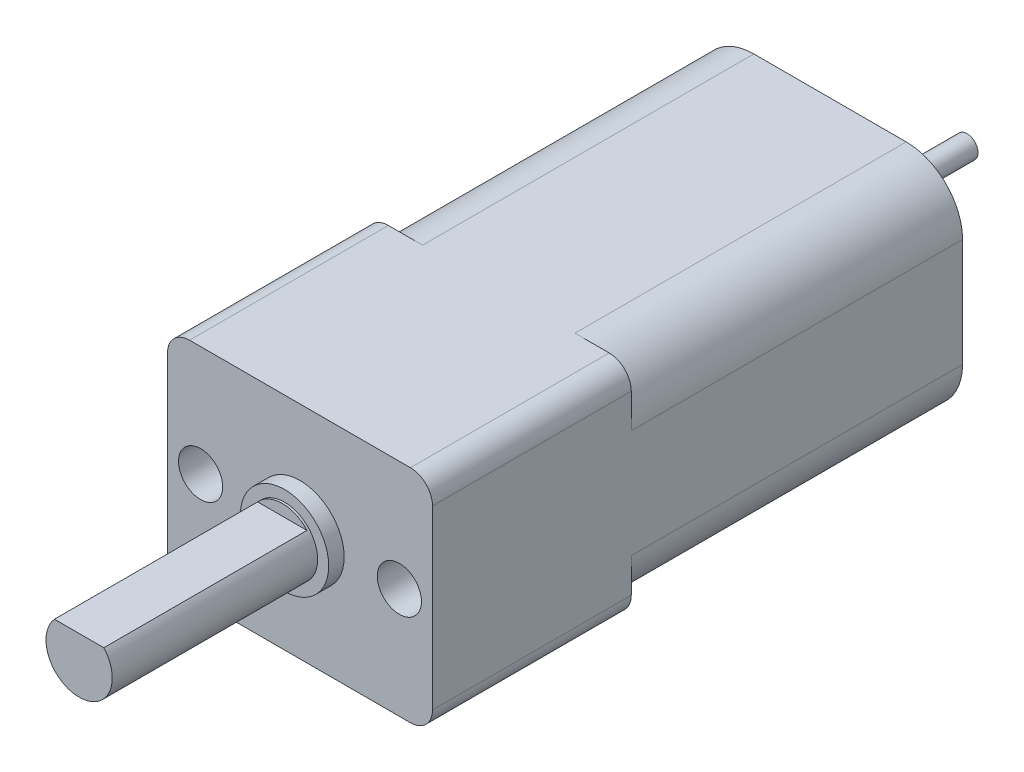
SolidWorks part; units mm, degrees
ref_plane "Front Plane" through (0, 0, 0) normal (0, 0, 1) x (1, 0, 0)
ref_plane "Top Plane" through (0, 0, 0) normal (0, 1, 0) x (1, 0, 0)
ref_plane "Right Plane" through (0, 0, 0) normal (1, 0, 0) x (0, 0, -1)
sketch "Sketch1" plane through (0, 0, 0) normal (0, 0, 1) x (1, 0, 0)
  line L1 (3.45, -5) -> (-3.45, -5)
  line L2 (6, -2.45) -> (6, 2.45)
  line L3 (3.45, 5) -> (-3.45, 5)
  line L4 (-6, -2.45) -> (-6, 2.45)
  line L5 (6, -5) -> (-6, 5) construction
  line L6 (6, 5) -> (-6, -5) construction
  arc A0 (3.45, 5) -> (6, 2.45) centre (3.45, 2.45) cw
  arc A1 (6, -2.45) -> (3.45, -5) centre (3.45, -2.45) cw
  arc A2 (-6, -2.45) -> (-3.45, -5) centre (-3.45, -2.45) ccw
  arc A3 (-3.45, 5) -> (-6, 2.45) centre (-3.45, 2.45) ccw
  point P0 (0, 0)
  dimension "D3" = 2.55
  dimension "D1" = 12
  dimension "D2" = 10
extrude "Boss-Extrude1" add sketch "Sketch1" along normal blind 15
sketch "Sketch2" plane through (0, 0, 15) normal (0, 0, 1) x (1, 0, 0)
  line L1 (5, -5) -> (-5, -5)
  line L2 (6, -4) -> (6, 4)
  line L3 (5, 5) -> (-5, 5)
  line L4 (-6, -4) -> (-6, 4)
  line L5 (6, -5) -> (-6, 5) construction
  line L6 (6, 5) -> (-6, -5) construction
  arc A0 (-6, -4) -> (-5, -5) centre (-5, -4) ccw
  arc A1 (5, -5) -> (6, -4) centre (5, -4) ccw
  arc A2 (6, 4) -> (5, 5) centre (5, 4) ccw
  arc A3 (-5, 5) -> (-6, 4) centre (-5, 4) ccw
  point P0 (0, 0)
  dimension "D3" = 1
  dimension "D1" = 12
  dimension "D2" = 10
extrude "Boss-Extrude2" add sketch "Sketch2" along normal blind 9
sketch "Sketch3" plane through (0, 0, 24) normal (0, 0, 1) x (1, 0, 0)
  circle A0 centre (0, 0) radius 2
  dimension "D1" = 4
extrude "Boss-Extrude3" add sketch "Sketch3" along normal blind 0.7
sketch "Sketch4" plane through (0, 0, 24.7) normal (0, 0, 1) x (1, 0, 0)
  circle A0 centre (0, 0) radius 1.5
  dimension "D1" = 3
extrude "Boss-Extrude4" add sketch "Sketch4" along normal blind 9.3
sketch "Sketch5" plane through (0, 0, 34) normal (0, 0, 1) x (1, 0, 0)
  line L0 (0, 0) -> (0, 1.5) construction
  line L2 (1.5, 1) -> (-1.5, 1)
  line L3 (1.5, 1) -> (1.5, 2)
  line L4 (1.5, 2) -> (-1.5, 2)
  line L5 (-1.5, 1) -> (-1.5, 2)
  line L6 (1.5, 1) -> (-1.5, 2) construction
  line L7 (1.5, 2) -> (-1.5, 1) construction
  dimension "D1" = 1.5
  dimension "D2" = 3
  dimension "D3" = 1
extrude "Cut-Extrude1" cut sketch "Sketch5" against normal blind 9.2
sketch "Sketch6" plane through (0, 0, 0) normal (0, 0, -1) x (-1, 0, 0)
  circle A0 centre (0, 0) radius 2.5
  dimension "D1" = 5
extrude "Boss-Extrude5" add sketch "Sketch6" along normal blind 1.2
sketch "Sketch7" plane through (0, 0, -1.2) normal (0, 0, -1) x (-1, 0, 0)
  circle A0 centre (0, 0) radius 0.5
  dimension "D1" = 1
extrude "Boss-Extrude6" add sketch "Sketch7" along normal blind 5
sketch "Sketch9" plane through (0, 0, 24) normal (0, 0, 1) x (1, 0, 0)
  line L0 (0, 0) -> (4.5, 0) construction
  line L1 (0, 0) -> (-4.5, 0) construction
  dimension "D1" = 4.5
  dimension "D2" = 4.5
hole_wizard "M1.6 Clearance Hole1" positions "Sketch11" profile "Sketch12" hole size "M1.6" standard "ISO"
sketch "Sketch11" plane through (0, 0, 24) normal (0, 0, 1) x (1, 0, 0)
  point P0 (-4.5, 0)
  point P3 (4.5, 0)
sketch "Sketch12" plane through (-4.5, 0, 24) normal (1, 0, 0) x (0, -1, 0)
  line L0 (0, 0) -> (0, 7.6009)
  line L1 (0, 7.6009) -> (1, 7)
  line L2 (1, 7) -> (1, 0)
  line L5 (1, 0) -> (0, 0)
  line L10 (0, 7.6009) -> (-1, 7) construction
  line L11 (0, -6.35) -> (0, 107.95) construction
  dimension "Hole Dia." = 2
  dimension "Hole Depth" = 7
  dimension "Drill Angle" = 118
